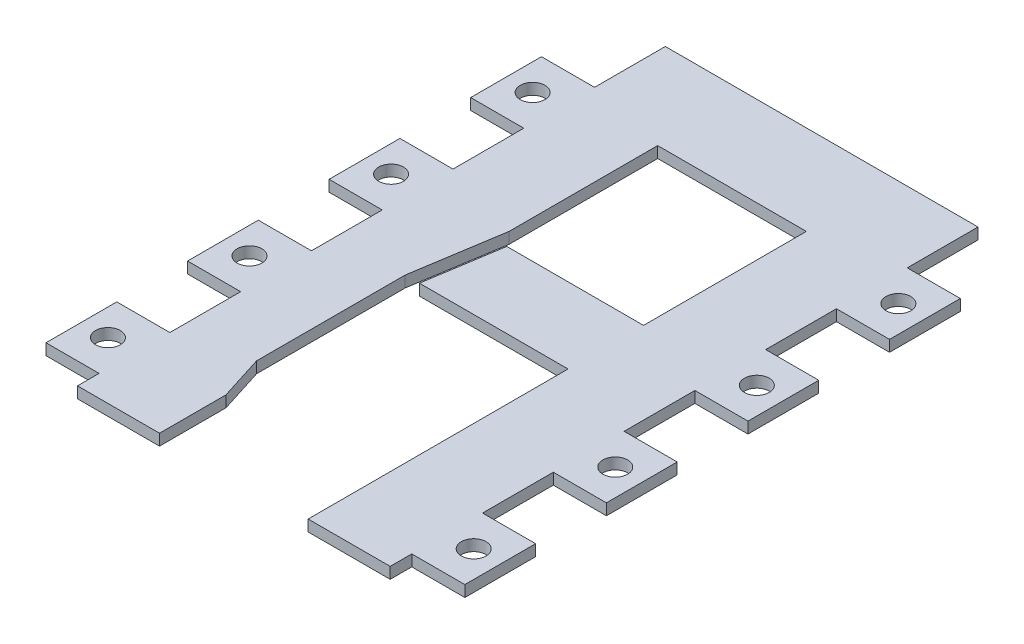
SolidWorks part; units mm, degrees
ref_plane "Front Plane" through (0, 0, 0) normal (0, 0, 1) x (1, 0, 0)
ref_plane "Top Plane" through (0, 0, 0) normal (0, 1, 0) x (1, 0, 0)
ref_plane "Right Plane" through (0, 0, 0) normal (1, 0, 0) x (0, 0, -1)
sketch "Sketch1" plane through (0, 0, 0) normal (0, 1, 0) x (1, 0, 0)
  line L0 (44.175, 25.3333) -> (44.175, 0) construction
  line L1 (0, 0) -> (88.35, 0)
  line L2 (0, 0) -> (0, 160)
  line L3 (0, 160) -> (88.35, 160)
  line L4 (88.35, 0) -> (88.35, 160)
  line L5 (23.175, 134.6667) -> (65.175, 134.6667)
  line L6 (23.175, 134.6667) -> (23.175, 92.6667)
  line L7 (23.175, 92.6667) -> (65.175, 92.6667)
  line L8 (65.175, 134.6667) -> (65.175, 92.6667)
  line L9 (23.175, 67.3333) -> (65.175, 67.3333)
  line L10 (23.175, 67.3333) -> (23.175, 25.3333)
  line L11 (23.175, 25.3333) -> (65.175, 25.3333)
  line L12 (65.175, 67.3333) -> (65.175, 25.3333)
  line L13 (44.175, 134.6667) -> (44.175, 160) construction
  line L14 (44.175, 67.3333) -> (44.175, 92.6667) construction
  line L15 (23.175, 92.6667) -> (19.175, 67.3333)
  line L16 (23.175, 25.3333) -> (27.175, 25.3333)
  line L17 (23.175, 25.3333) -> (23.175, 0)
  line L18 (23.175, 0) -> (27.175, 0)
  line L19 (27.175, 25.3333) -> (27.175, 0)
  line L20 (65.175, 25.3333) -> (61.175, 25.3333)
  line L21 (65.175, 25.3333) -> (65.175, 0)
  line L22 (65.175, 0) -> (61.175, 0)
  line L23 (61.175, 25.3333) -> (61.175, 0)
  line L24 (19.175, 67.3333) -> (19.175, 25.3333)
  line L25 (19.175, 25.3333) -> (23.175, 12.6667)
  line L26 (27.175, 92.6667) -> (23.175, 67.3333)
  line L27 (19.175, 67.3333) -> (23.175, 67.3333) construction
  line L28 (27.175, 92.6667) -> (23.175, 92.6667)
  line L29 (23.175, 12.6667) -> (23.175, 25.3333)
  line L30 (65.175, 92.6667) -> (65.175, 88.6667)
  line L31 (65.175, 88.6667) -> (26.5434, 88.6667)
  point P13 (44.175, 67.3333)
  point P14 (44.175, 92.6667)
  point P15 (44.175, 134.6667)
  point P16 (44.175, 160)
  dimension "D1" = 88.35
  dimension "D2" = 160
  dimension "D3" = 42
  dimension "D4" = 4
extrude "Boss-Extrude1" add sketch "Sketch1" along normal blind 3.175 contours L30 L31 L26 L9 L12 L21 L1 L4 L3 L2 L17 L25 L24 L15 L6 L5 L8
sketch "Sketch3" plane through (0, 3.175, 0) normal (0, 1, 0) x (1, 0, 0)
  line L0 (0, 0) -> (0, 160) construction
  line L1 (0, 140) -> (-15, 140)
  line L2 (0, 140) -> (0, 120)
  line L3 (0, 120) -> (-15, 120)
  line L4 (-15, 140) -> (-15, 120)
  line L5 (0, 100) -> (0, 80)
  line L6 (0, 100) -> (-15, 100)
  line L7 (-15, 100) -> (-15, 80)
  line L8 (0, 80) -> (-15, 80)
  line L9 (0, 60) -> (0, 40)
  line L10 (0, 60) -> (-15, 60)
  line L11 (-15, 60) -> (-15, 40)
  line L12 (0, 40) -> (-15, 40)
  line L13 (0, 20) -> (0, 0)
  line L14 (0, 20) -> (-15, 20)
  line L15 (-15, 20) -> (-15, 0)
  line L16 (0, 0) -> (-15, 0)
  line L17 (-15, 0) -> (-15, -20) construction
  line L19 (44.175, 160) -> (44.175, 134.6667) construction
  line L20 (0, 160) -> (88.35, 160) construction
  line L21 (23.175, 134.6667) -> (65.175, 134.6667) construction
  line L22 (103.35, 0) -> (103.35, -20) construction
  line L23 (88.35, 0) -> (103.35, 0)
  line L24 (103.35, 20) -> (103.35, 0)
  line L25 (88.35, 20) -> (103.35, 20)
  line L26 (88.35, 20) -> (88.35, 0)
  line L27 (88.35, 40) -> (103.35, 40)
  line L28 (103.35, 60) -> (103.35, 40)
  line L29 (88.35, 60) -> (103.35, 60)
  line L30 (88.35, 60) -> (88.35, 40)
  line L31 (88.35, 80) -> (103.35, 80)
  line L32 (103.35, 100) -> (103.35, 80)
  line L33 (88.35, 100) -> (103.35, 100)
  line L34 (88.35, 100) -> (88.35, 80)
  line L35 (103.35, 140) -> (103.35, 120)
  line L36 (88.35, 120) -> (103.35, 120)
  line L37 (88.35, 140) -> (88.35, 120)
  line L38 (88.35, 140) -> (103.35, 140)
  line L39 (-15, 140) -> (-15, 160) construction
  circle A0 centre (-7.5, 130) radius 3.5
  circle A1 centre (-7.5, 90) radius 3.5
  circle A2 centre (-7.5, 50) radius 3.5
  circle A3 centre (-7.5, 10) radius 3.5
  circle A4 centre (95.85, 10) radius 3.5
  circle A5 centre (95.85, 50) radius 3.5
  circle A6 centre (95.85, 90) radius 3.5
  circle A7 centre (95.85, 130) radius 3.5
  point P6 (-7.5, 140)
  point P12 (-15, 130)
  point P30 (0, 0)
  dimension "D3" = 7
  dimension "D1" = 20
  dimension "D2" = 15
  dimension "D4" = 4
extrude "Boss-Extrude3" add sketch "Sketch3" against normal up to surface (3.175 mm away) up to face at (38.6355, 0, -68.7083)
sketch "Sketch4" plane through (0, 3.175, 0) normal (0, 1, 0) x (1, 0, 0)
  line L0 (-15, 0) -> (23.175, 0) construction
  line L1 (0, 0) -> (23.175, 0)
  line L2 (0, 0) -> (0, -6.096)
  line L3 (0, -6.096) -> (23.175, -6.096)
  line L4 (23.175, 0) -> (23.175, -6.096)
  line L5 (65.175, 0) -> (103.35, 0) construction
  line L6 (65.175, 0) -> (88.35, 0)
  line L7 (65.175, 0) -> (65.175, -6.096)
  line L8 (65.175, -6.096) -> (88.35, -6.096)
  line L9 (88.35, 0) -> (88.35, -6.096)
  point P11 (23.175, 0)
  point P13 (78.8835, 0)
  point P16 (9.2368, -27.0449)
  point P17 (23.175, -8.1089)
  dimension "D1" = 88.35
  dimension "D2" = 6.096
extrude "Boss-Extrude4" add sketch "Sketch4" against normal up to surface (3.175 mm away) up to face at (42.1606, 0, -75.8939)
